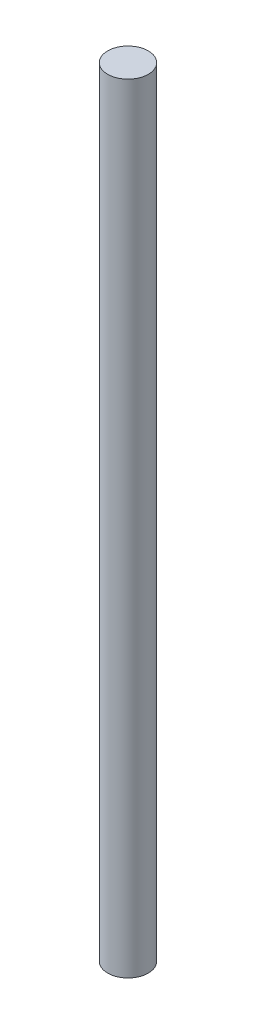
SolidWorks part; units mm, degrees
material "Cast Stainless Steel"
ref_plane "Ön Düzlem" through (0, 0, 0) normal (0, 0, 1) x (1, 0, 0)
ref_plane "Üst Düzlem" through (0, 0, 0) normal (0, 1, 0) x (1, 0, 0)
ref_plane "Sağ Düzlem" through (0, 0, 0) normal (1, 0, 0) x (0, 0, -1)
sketch "Sketch1" plane through (0, 0, 0) normal (0, 1, 0) x (1, 0, 0)
  circle A0 centre (0, 0) radius 6
  dimension "D1" = 12
extrude "Boss-Extrude1" add sketch "Sketch1" along normal blind 230
